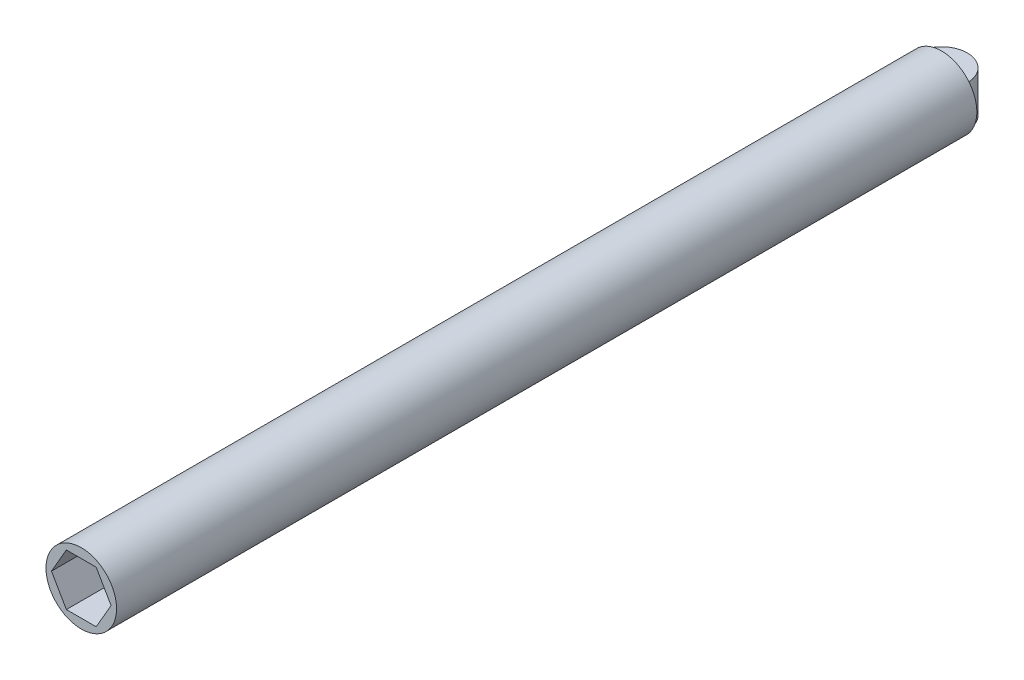
SolidWorks part; units mm, degrees
ref_plane "Front Plane" through (0, 0, 0) normal (0, 0, 1) x (1, 0, 0)
ref_plane "Top Plane" through (0, 0, 0) normal (0, 1, 0) x (1, 0, 0)
ref_plane "Right Plane" through (0, 0, 0) normal (1, 0, 0) x (0, 0, -1)
sketch "Sketch1" plane through (0, 0, 0) normal (0, 0, 1) x (1, 0, 0)
  circle A0 centre (0, 0) radius 1.025
  dimension "D1" = 2.05
extrude "Boss-Extrude1" add sketch "Sketch1" along normal blind 12
sketch "Sketch2" plane through (0, 0, 12) normal (0, 0, 1) x (1, 0, 0)
  line L0 (0, 0) -> (1.025, 0)
  line L2 (0.866, 0) -> (0.433, 0.75)
  line L3 (0.433, 0.75) -> (-0.433, 0.75)
  line L4 (-0.433, 0.75) -> (-0.866, 0)
  line L5 (-0.866, 0) -> (-0.433, -0.75)
  line L6 (-0.433, -0.75) -> (0.433, -0.75)
  line L7 (0.433, -0.75) -> (0.866, 0)
  circle A0 centre (0, 0) radius 1.025 construction
  circle A1 centre (0, 0) radius 0.75 construction
extrude "Cut-Extrude1" cut sketch "Sketch2" against normal blind 7
sketch "Sketch3" plane through (0, 0, 0) normal (0, 0, -1) x (-1, 0, 0)
  circle A0 centre (0, 0) radius 1.025
extrude "Boss-Extrude2" add sketch "Sketch3" along normal blind 4
sketch "Sketch4" plane through (0, 0, -4) normal (0, 0, -1) x (-1, 0, 0)
  line L0 (0, 0) -> (1.025, 0)
  circle A0 centre (0, 0) radius 1.025 construction
ref_plane "Plane3" through (0, 0, 0) normal (0, 1, 0) x (1, 0, 0)
sketch "Sketch5" plane through (0, 0, 0) normal (0, 1, 0) x (1, 0, 0)
  line L0 (1.025, 4) -> (-1.025, 4) construction
  line L1 (-1, 4) -> (1, 4)
  circle A0 centre (0, 4) radius 1
  dimension "D1" = 2
sketch "Sketch6" plane through (0, 0, 12) normal (0, 0, 1) x (1, 0, 0)
  line L1 (0.866, 0) -> (0.433, 0.75)
  line L2 (0.433, 0.75) -> (-0.433, 0.75)
  line L3 (-0.433, 0.75) -> (-0.866, 0)
  line L4 (-0.866, 0) -> (-0.433, -0.75)
  line L5 (-0.433, -0.75) -> (0.433, -0.75)
  line L6 (0.433, -0.75) -> (0.866, 0)
  circle A0 centre (0, 0) radius 0.75 construction
  circle A1 centre (0, 0) radius 1.025
extrude "Boss-Extrude5" add sketch "Sketch6" along normal blind 7
sketch "Sketch7" plane through (0, 0, -4) normal (0, 0, -1) x (-1, 0, 0)
  circle A0 centre (0, 0) radius 1.025
extrude "Boss-Extrude6" add sketch "Sketch7" along normal blind 2
sketch "Sketch8" plane through (0, 0, 0) normal (0, 1, 0) x (1, 0, 0)
  line L0 (1.025, 6) -> (-1.025, 6) construction
  line L1 (-0.75, 6) -> (0.75, 6)
  circle A0 centre (0, 6) radius 0.75
  dimension "D1" = 1.5
extrude "Boss-Extrude8" add sketch "Sketch8" along normal blind 0.6 and the other way blind 0.6 contours L1 A0
